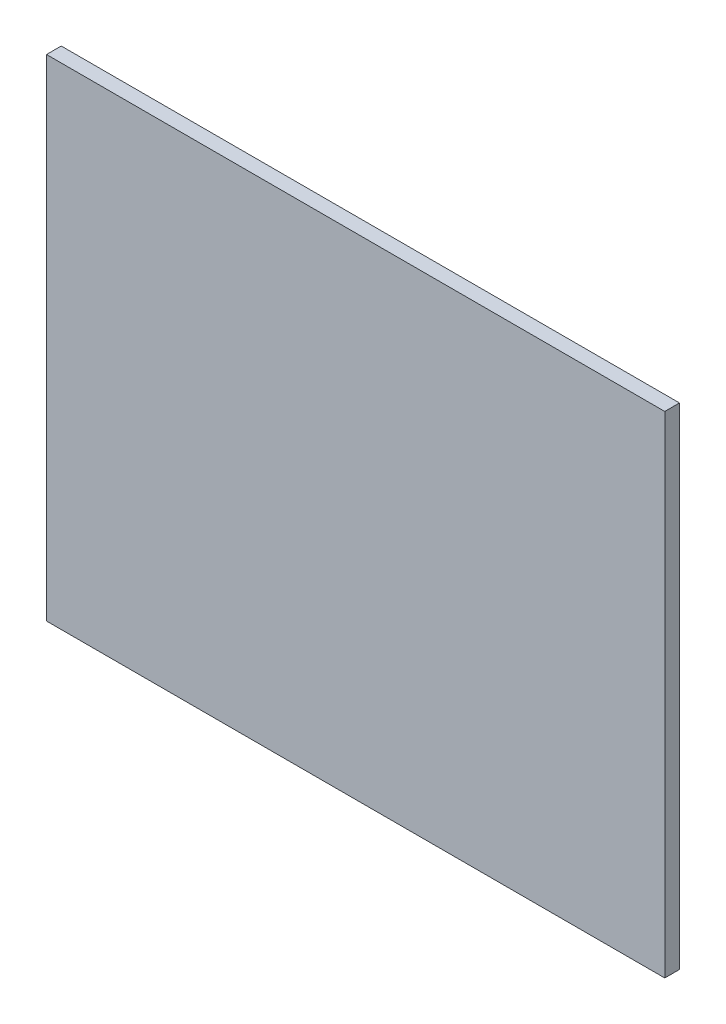
SolidWorks part; units mm, degrees
ref_plane "Front Plane" through (0, 0, 0) normal (0, 0, 1) x (1, 0, 0)
ref_plane "Top Plane" through (0, 0, 0) normal (0, 1, 0) x (1, 0, 0)
ref_plane "Right Plane" through (0, 0, 0) normal (1, 0, 0) x (0, 0, -1)
sketch "Sketch1" plane through (0, 0, 0) normal (0, 0, 1) x (1, 0, 0)
  line L1 (-25.6639, -23.8872) -> (37.3361, -23.8872)
  line L2 (-25.6639, -23.8872) -> (-25.6639, 26.1128)
  line L3 (-25.6639, 26.1128) -> (37.3361, 26.1128)
  line L4 (37.3361, -23.8872) -> (37.3361, 26.1128)
  dimension "D1" = 63
  dimension "D2" = 50
extrude "Boss-Extrude1" add sketch "Sketch1" along normal blind 1.5
